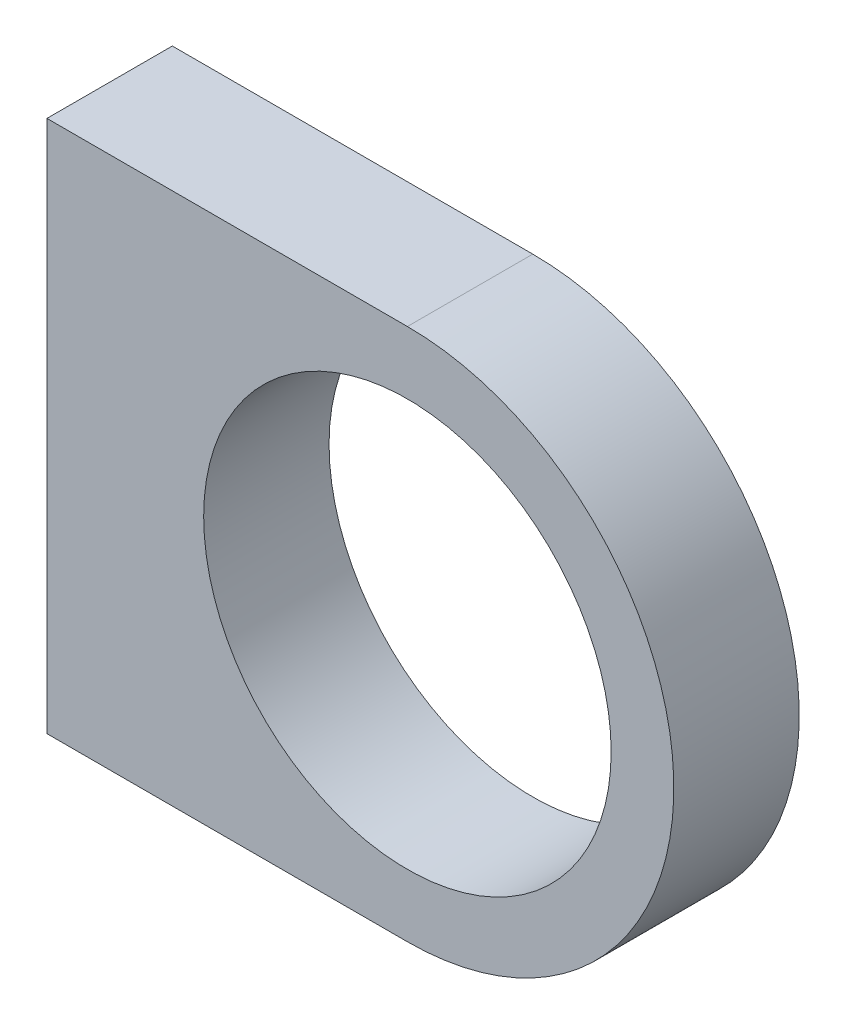
SolidWorks part; units mm, degrees
ref_plane "Front Plane" through (0, 0, 0) normal (0, 0, 1) x (1, 0, 0)
ref_plane "Top Plane" through (0, 0, 0) normal (0, 1, 0) x (1, 0, 0)
ref_plane "Right Plane" through (0, 0, 0) normal (1, 0, 0) x (0, 0, -1)
sketch "Sketch2" plane through (0, 0, 0) normal (0, 0, 1) x (1, 0, 0)
  line L4 (22.9129, 16.376) -> (22.9129, -18.1515) construction
  line L5 (22.9129, 16.1123) -> (-0.0871, 16.1123)
  line L6 (22.9129, -17.8877) -> (-0.0871, -17.8877)
  line L7 (-0.0871, 16.1123) -> (-0.0871, -17.8877)
  circle A0 centre (22.9129, -0.8877) radius 13
  arc A2 (22.9129, -17.8877) -> (22.9129, 16.1123) centre (22.9129, -0.8877) ccw
  dimension "D3" = 26
  dimension "D4" = 23
  dimension "D1" = 34
  dimension "D2" = 23
extrude "Boss-Extrude1" add sketch "Sketch2" along normal blind 8
